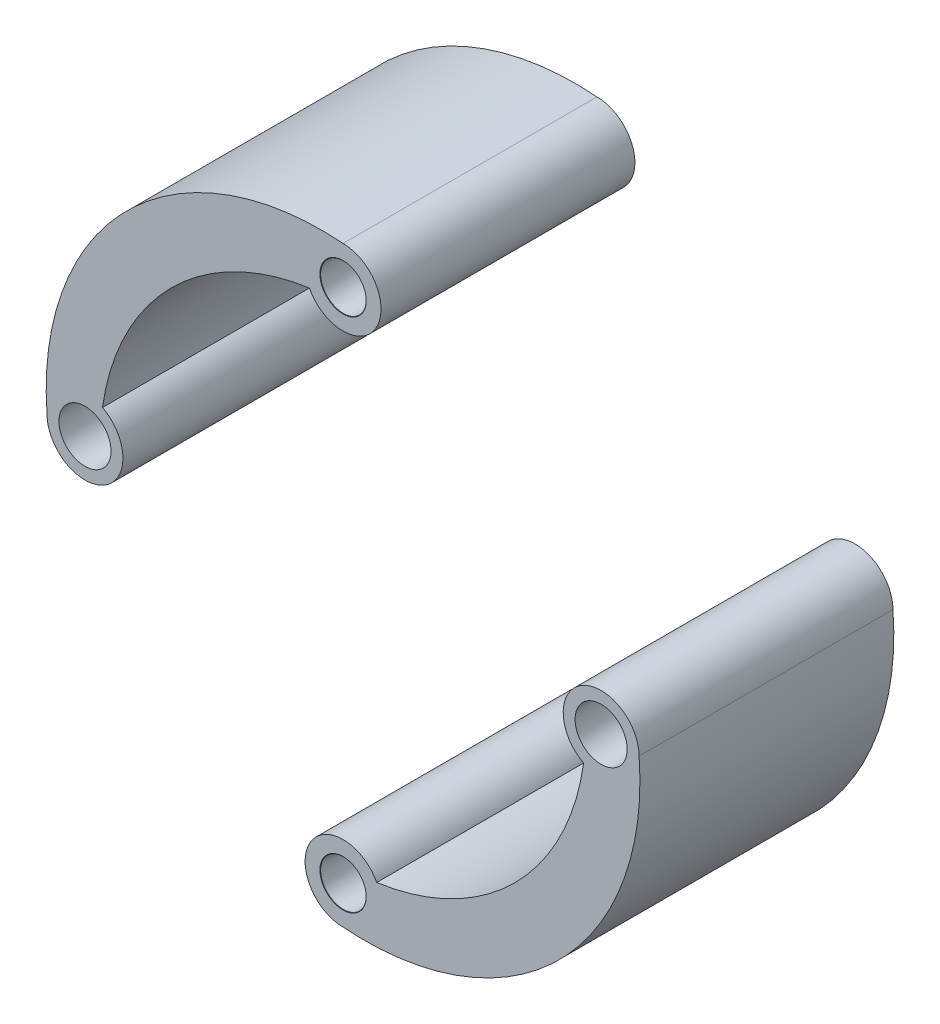
SolidWorks part; units mm, degrees
ref_plane "Front Plane" through (0, 0, 0) normal (1, 0, 0) x (0, 1, 0)
ref_plane "Top Plane" through (0, 0, 0) normal (0, 0, 1) x (0, 1, 0)
ref_plane "Right Plane" through (0, 0, 0) normal (0, 1, 0) x (-1, 0, 0)
sketch "Sketch1" plane through (0, 0, 0) normal (0, 0, 1) x (0, 1, 0)
  line L0 (0, -17) -> (0, 17) construction
  line L1 (-17, 0) -> (17, 0) construction
  line L2 (0, 0) -> (1.4142, 1.4142) construction
  line L3 (0, 0) -> (-1.4142, -1.4142) construction
  circle A0 centre (0, 17) radius 2.5
  circle A1 centre (0, -17) radius 2.5
  circle A2 centre (-17, 0) radius 2.5
  circle A3 centre (17, 0) radius 2.5
  arc A4 (0, 19.5) -> (19.5, 0) centre (1.4142, 1.4142) cw
  arc A5 (2.2175, 15.8456) -> (15.8456, 2.2175) centre (0, 0) cw
  arc A6 (-19.5, 0) -> (0, -19.5) centre (-1.4142, -1.4142) ccw
  arc A7 (-2.2175, -15.8456) -> (-15.8456, -2.2175) centre (0, 0) cw
  circle A8 centre (0, 0) radius 13.75 construction
  point P4 (0, 0)
  point P8 (0, 0)
  dimension "D3" = 5
  dimension "D4" = 5
  dimension "D5" = 16
  dimension "D6" = 45
  dimension "D7" = 16
  dimension "D8" = 2
  dimension "D9" = 27.5
  dimension "D1" = 34
  dimension "D2" = 34
  dimension "D10" = 2
extrude "Boss-Extrude1" add sketch "Sketch1" along normal blind 16.7224
hole_wizard "Ø3.0mm Dowel Hole1" positions "Sketch3" profile "Sketch5" hole size "Ø3.0" standard "ANSI Metric" end condition through all
sketch "Sketch3" plane through (0, 0, 16.7224) normal (0, 0, 1) x (1, 0, 0)
  point P0 (0, 17)
  point P3 (0, -17)
sketch "Sketch5" plane through (0, 17, 16.7224) normal (1, 0, 0) x (0, -1, 0)
  line L0 (0, 0) -> (0, 16.7224)
  line L1 (0, 16.7224) -> (1.5, 16.7224)
  line L2 (1.5, 16.7224) -> (1.5, 0.021)
  line L3 (1.5, 0.021) -> (1.525, 0)
  line L5 (1.525, 0) -> (0, 0)
  line L6 (-1.5, 0.021) -> (-1.525, 0) construction
  line L11 (0, -6.35) -> (0, 107.95) construction
  dimension "Thru Hole Dia." = 3
  dimension "Thru Hole Depth" = 16.7224
  dimension "Near C'Sink Dia." = 3.05
  dimension "Near C'Sink Angle" = 100
sketch "Sketch6" plane through (0, 0, 16.7224) normal (0, 0, 1) x (1, 0, 0)
  circle A0 centre (-17, 0) radius 1.715
  circle A1 centre (17, 0) radius 1.715
  dimension "D1" = 3.43
extrude "Cut-Extrude1" cut sketch "Sketch6" against normal blind 5
sketch "Sketch7" plane through (0, 0, 0) normal (0, 0, -1) x (1, 0, 0)
  circle A0 centre (-17, 0) radius 1.715
  circle A1 centre (17, 0) radius 1.715
  dimension "D1" = 3.43
extrude "Cut-Extrude2" cut sketch "Sketch7" against normal blind 5
equation "\"Alum Bracket Thickness\"= 0.35in"
equation "\"D1@Boss-Extrude1\"=28-\"Alum Bracket Thickness\"-\"spur gear gap\""
equation "\"spur gear gap\"= 0.094in"
